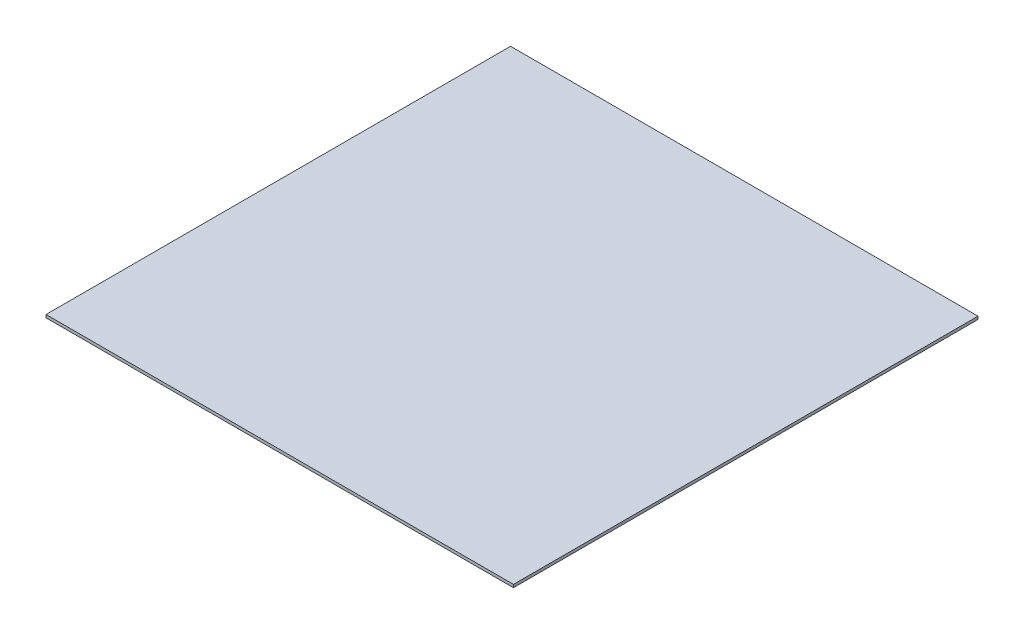
SolidWorks part; units mm, degrees
ref_plane "Front Plane" through (0, 0, 0) normal (0, 0, 1) x (1, 0, 0)
ref_plane "Top Plane" through (0, 0, 0) normal (0, 1, 0) x (1, 0, 0)
ref_plane "Right Plane" through (0, 0, 0) normal (1, 0, 0) x (0, 0, -1)
sketch "Sketch1" plane through (0, 0, 0) normal (0, 1, 0) x (1, 0, 0)
  line L1 (-402.5, 400) -> (402.5, 400)
  line L2 (-402.5, 400) -> (-402.5, -400)
  line L3 (-402.5, -400) -> (402.5, -400)
  line L4 (402.5, 400) -> (402.5, -400)
  line L5 (-402.5, 400) -> (402.5, -400) construction
  line L6 (-402.5, -400) -> (402.5, 400) construction
  point P0 (0, 0)
  dimension "D1" = 805
  dimension "D2" = 800
extrude "Boss-Extrude1" add sketch "Sketch1" along normal blind 5
